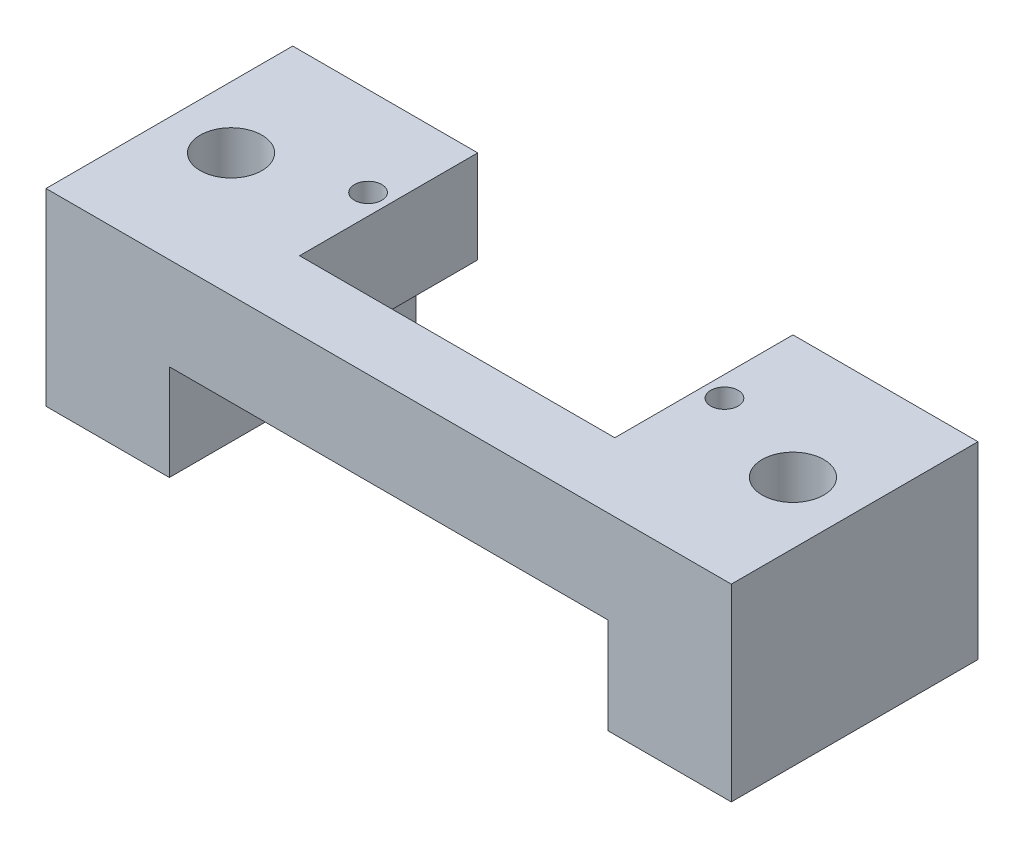
SolidWorks part; units mm, degrees
material "PVC 0.007 Plasticized"
ref_plane "Front Plane" through (0, 0, 0) normal (0, 0, 1) x (1, 0, 0)
ref_plane "Top Plane" through (0, 0, 0) normal (0, 1, 0) x (1, 0, 0)
ref_plane "Right Plane" through (0, 0, 0) normal (1, 0, 0) x (0, 0, -1)
sketch "Sketch1" plane through (0, 0, 0) normal (0, 1, 0) x (1, 0, 0)
  line L1 (0, 0) -> (50, 0)
  line L2 (0, 0) -> (0, 18)
  line L3 (0, 18) -> (50, 18)
  line L4 (50, 0) -> (50, 18)
  dimension "D1" = 50
  dimension "D2" = 18
extrude "Boss-Extrude2" add sketch "Sketch1" along normal blind 22
sketch "Sketch4" plane through (0, 0, 0) normal (0, 0, 1) x (1, 0, 0)
  line L0 (25, 0) -> (25, 22) construction
  line L1 (0, 0) -> (50, 0) construction
  line L2 (0, 22) -> (50, 22) construction
  line L4 (9, -7) -> (41, -7)
  line L5 (9, -7) -> (9, 7)
  line L6 (9, 7) -> (41, 7)
  line L7 (41, -7) -> (41, 7)
  line L8 (9, -7) -> (41, 7) construction
  line L9 (9, 7) -> (41, -7) construction
  dimension "D1" = 32
  dimension "D2" = 14
extrude "Cut-Extrude1" cut sketch "Sketch4" against normal through all
sketch "Sketch5" plane through (0, 0, -18) normal (0, 0, -1) x (-1, 0, 0)
  line L0 (-25, 7) -> (-25, 22) construction
  line L1 (-41, 7) -> (-9, 7) construction
  line L2 (-50, 22) -> (0, 22) construction
  line L4 (-36.5, -2) -> (-13.5, -2)
  line L5 (-36.5, -2) -> (-36.5, 16)
  line L6 (-36.5, 16) -> (-13.5, 16)
  line L7 (-13.5, -2) -> (-13.5, 16)
  line L8 (-36.5, -2) -> (-13.5, 16) construction
  line L9 (-36.5, 16) -> (-13.5, -2) construction
  dimension "D1" = 23
  dimension "D2" = 18
extrude "Cut-Extrude3" cut sketch "Sketch5" against normal blind 13
sketch "Sketch6" plane through (0, 22, 0) normal (0, 1, 0) x (1, 0, 0)
sketch "Sketch7" plane through (0, 0, -18) normal (0, 0, -1) x (-1, 0, 0)
  line L0 (-50, 22) -> (-50, 0) construction
  line L1 (-50, 22) -> (0, 22)
  line L2 (-50, 22) -> (-50, 13.765)
  line L3 (-50, 13.765) -> (0, 13.765)
  line L4 (0, 22) -> (0, 13.765)
  line L5 (0, 22) -> (0, 0) construction
extrude "Cut-Extrude4" cut sketch "Sketch7" against normal through all
sketch "Sketch9" plane through (0, 7, 0) normal (0, -1, 0) x (1, 0, 0)
  circle A0 centre (12, -11.5) radius 1
  circle A1 centre (38, -11.5) radius 1
extrude "Cut-Extrude6" cut sketch "Sketch9" against normal through all
sketch "Sketch10" plane through (0, 13.765, 0) normal (0, 1, 0) x (1, 0, 0)
  line L0 (0, 9) -> (50, 9) construction
  line L1 (0, 0) -> (0, 18) construction
  line L2 (50, 0) -> (50, 18) construction
  line L3 (25, 9) -> (25, 20.1516) construction
  circle A0 centre (4.5, 9) radius 2.25
  circle A1 centre (45.5, 9) radius 2.25
  dimension "D1" = 4.5
  dimension "D2" = 4.5
extrude "Cut-Extrude7" cut sketch "Sketch10" against normal through all
